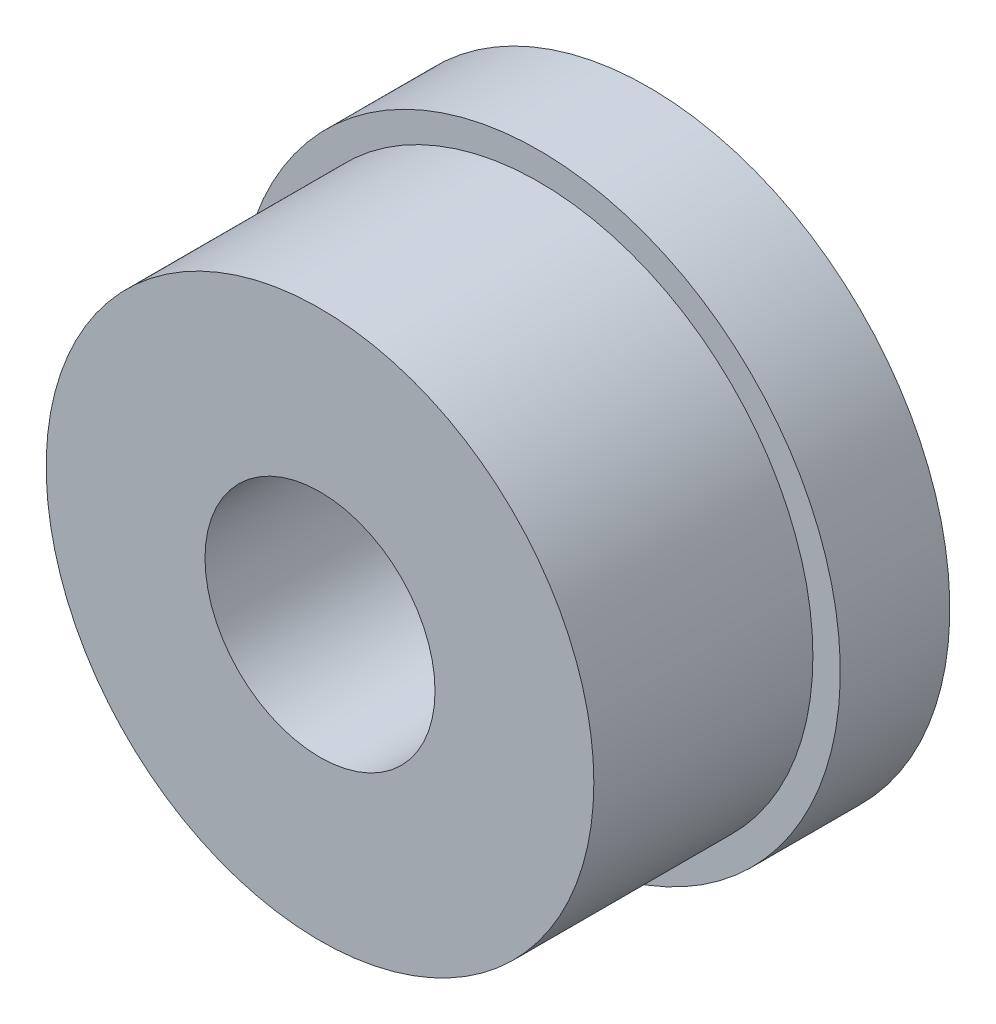
SolidWorks part; units mm, degrees
ref_plane "正面" through (0, 0, 0) normal (0, 0, 1) x (1, 0, 0)
ref_plane "平面" through (0, 0, 0) normal (0, 1, 0) x (1, 0, 0)
ref_plane "右側面" through (0, 0, 0) normal (1, 0, 0) x (0, 0, -1)
sketch "ｽｹｯﾁ1" plane through (0, 0, 0) normal (0, 0, 1) x (1, 0, 0)
  circle A0 centre (0, 0) radius 5
  dimension "D1" = 10
extrude "ﾎﾞｽ - 押し出し1" add sketch "ｽｹｯﾁ1" along normal blind 4
sketch "ｽｹｯﾁ2" plane through (0, 0, 0) normal (0, 0, -1) x (-1, 0, 0)
  circle A0 centre (0, 0) radius 5.5
  dimension "D1" = 11
extrude "ﾎﾞｽ - 押し出し2" add sketch "ｽｹｯﾁ2" along normal blind 2 contours A0
sketch "ｽｹｯﾁ3" plane through (0, 0, 4) normal (0, 0, 1) x (1, 0, 0)
  circle A0 centre (0, 0) radius 2.1
  dimension "D1" = 4.2
extrude "ｶｯﾄ - 押し出し1" cut sketch "ｽｹｯﾁ3" against normal through all
sketch "ｽｹｯﾁ4" plane through (0, 0, -2) normal (0, 0, -1) x (-1, 0, 0)
  circle A0 centre (0, 0) radius 4
  dimension "D1" = 8
extrude "ｶｯﾄ - 押し出し2" cut sketch "ｽｹｯﾁ4" against normal blind 3
